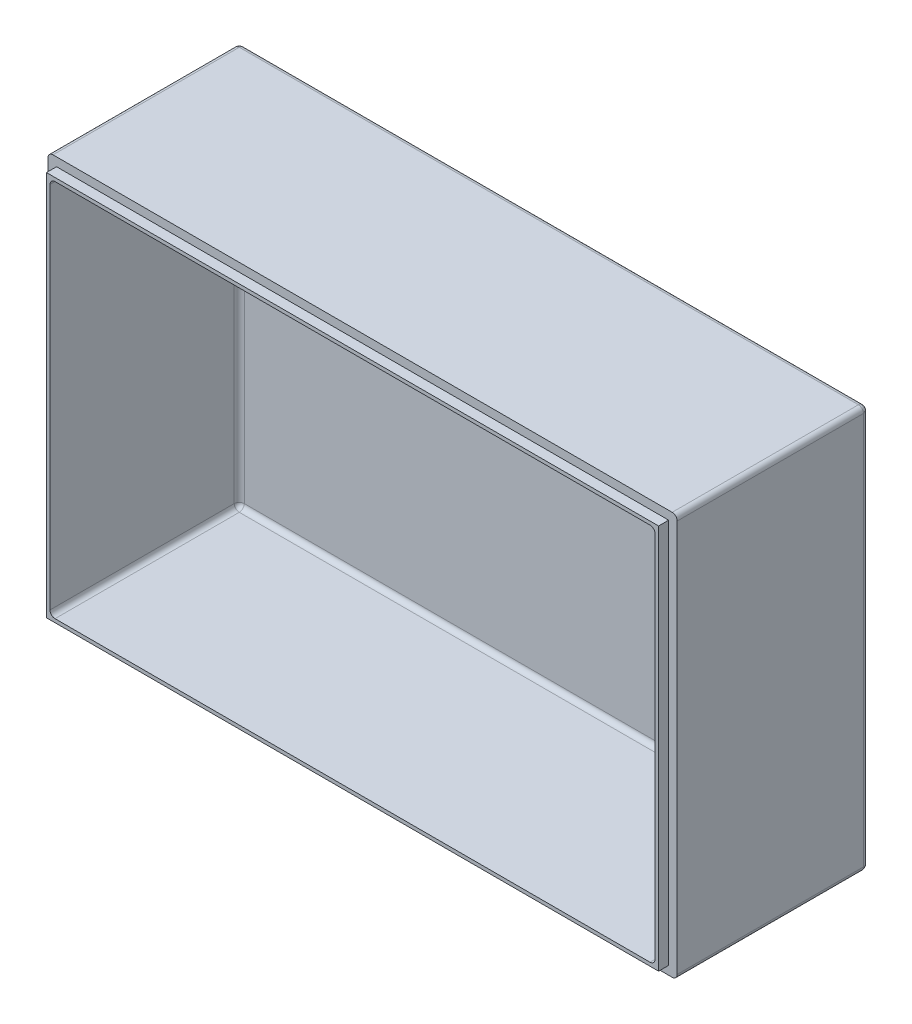
SolidWorks part; units mm, degrees
material "Резина"
ref_plane "Спереди" through (0, 0, 0) normal (0, 0, 1) x (1, 0, 0)
ref_plane "Сверху" through (0, 0, 0) normal (0, 1, 0) x (1, 0, 0)
ref_plane "Справа" through (0, 0, 0) normal (1, 0, 0) x (0, 0, -1)
sketch "Эскиз1" plane through (0, 0, 0) normal (0, 0, 1) x (1, 0, 0)
  line L1 (-62.5, 40) -> (62.5, 40)
  line L2 (-62.5, 40) -> (-62.5, -40)
  line L3 (-62.5, -40) -> (62.5, -40)
  line L4 (62.5, 40) -> (62.5, -40)
  line L5 (-62.5, 40) -> (62.5, -40) construction
  line L6 (-62.5, -40) -> (62.5, 40) construction
  point P0 (0, 0)
  dimension "D1" = 125
  dimension "D2" = 80
extrude "Бобышка-Вытянуть1" add sketch "Эскиз1" along normal blind 40
sketch "Эскиз2" plane through (0, 0, 40) normal (0, 0, 1) x (1, 0, 0)
  line L0 (62.5, 40) -> (-62.5, 40) construction
  line L1 (-60.1, 37.6) -> (60.1, 37.6)
  line L2 (-60.1, 37.6) -> (-60.1, -37.6)
  line L3 (-60.1, -37.6) -> (60.1, -37.6)
  line L4 (60.1, 37.6) -> (60.1, -37.6)
  line L5 (-60.1, 37.6) -> (60.1, -37.6) construction
  line L6 (-60.1, -37.6) -> (60.1, 37.6) construction
  line L7 (62.5, -40) -> (62.5, 40) construction
  point P0 (0, 0)
  dimension "D1" = 2.4
  dimension "D2" = 2.4
extrude "Вырез-Вытянуть1" cut sketch "Эскиз2" against normal blind 37.6
fillet "Скругление1" radius 1 8 edges at (62.5, -40, 20) (62.5, 40, 20) (62.5, 0, 0) (0, 40, 0) (-62.5, 40, 20) (-62.5, -40, 20) (0, -40, 0) (-62.5, 0, 0)
fillet "Скругление2" radius 1 8 edges at (60.1, 37.6, 21.2) (60.1, 0, 2.4) (60.1, -37.6, 21.2) (0, 37.6, 2.4) (-60.1, 37.6, 21.2) (0, -37.6, 2.4) (-60.1, -37.6, 21.2) (-60.1, 0, 2.4)
sketch "Эскиз3" plane through (0, 0, 0) normal (0, 0, -1) x (-1, 0, 0)
  line L0 (-61.5, 5) -> (59.5, 5) construction
  line L4 (-61.5, 39) -> (-61.5, -39) construction
  text T0 "Для\r\nЗСУ" font "Times New Roman" height 20
  dimension "D1" = 5
extrude "Вырез-Вытянуть2" [suppressed] cut sketch "Эскиз3" against normal blind 0.5
sketch "Эскиз4" plane through (62.5, 0, 0) normal (1, 0, 0) x (0, 0, -1)
  line L0 (0, 0) -> (-20.5, 0) construction
  line L1 (-20.5, -4) -> (-20.5, 4)
  line L2 (-20.5, 4) -> (-21.5858, 4)
  line L3 (-23.5, 2.0858) -> (-23.5, -2.0858)
  line L4 (-15.75, 0) -> (-20.5, 0) construction
  line L5 (-13, 6.5) -> (-18.5, 6.5)
  line L6 (-13, 6.5) -> (-13, -6.5)
  line L7 (-13, -6.5) -> (-18.5, -6.5)
  line L8 (-18.5, 6.5) -> (-18.5, -6.5)
  line L9 (-13, 6.5) -> (-18.5, -6.5) construction
  line L10 (-13, -6.5) -> (-18.5, 6.5) construction
  line L11 (-22.2929, 3.7071) -> (-23.2071, 2.7929)
  line L12 (-22.2929, -3.7071) -> (-23.2071, -2.7929)
  line L13 (-20.5, -4) -> (-21.5858, -4)
  arc A0 (-22.2929, -3.7071) -> (-21.5858, -4) centre (-21.5858, -3) ccw
  arc A1 (-23.2071, -2.7929) -> (-23.5, -2.0858) centre (-22.5, -2.0858) cw
  arc A2 (-23.2071, 2.7929) -> (-23.5, 2.0858) centre (-22.5, 2.0858) ccw
  arc A3 (-22.2929, 3.7071) -> (-21.5858, 4) centre (-21.5858, 3) cw
  point P5 (-15.75, 0)
  point P15 (-23.5, 0)
  point P18 (-22, -4)
  point P21 (-23.5, -2.5)
  point P24 (-23.5, 2.5)
  point P27 (-22, 4)
  dimension "D9" = 1
  dimension "D1" = 13
  dimension "D2" = 5.5
  dimension "D3" = 13
  dimension "D4" = 2
  dimension "D5" = 3
  dimension "D6" = 8
  dimension "D7" = 1.5
  dimension "D8" = 1.5
extrude "Вырез-Вытянуть3" [suppressed] cut sketch "Эскиз4" against normal blind 5
sketch "Эскиз5" plane through (60.1, 0, 0) normal (-1, 0, 0) x (0, 0, 1)
  line L0 (11.4, 0) -> (29.8169, 0) construction
  line L1 (11.4, 0) -> (11.4, -8.5)
  line L2 (11.4, -8.5) -> (13, -8.5)
  line L3 (13, -8.5) -> (13, 8.5)
  line L4 (11.4, 0) -> (11.4, 8.5)
  line L5 (11.4, 8.5) -> (13, 8.5)
  line L13 (0, -39) -> (0, 39) construction
  line L15 (11.4, -8.5) -> (21.4, -8.5)
  line L16 (11.4, -8.5) -> (11.4, -10.1)
  line L17 (11.4, -10.1) -> (21.4, -10.1)
  line L18 (21.4, -8.5) -> (21.4, -10.1)
  line L19 (11.4, -8.5) -> (21.4, -10.1) construction
  line L20 (11.4, -10.1) -> (21.4, -8.5) construction
  point P8 (16.4, -9.3)
  dimension "D1" = 1.6
  dimension "D2" = 17
  dimension "D3" = 8.5
  dimension "D4" = 13
  dimension "D5" = 17
  dimension "D6" = 1.6
  dimension "D7" = 10
  dimension "D8" = 11.4
extrude "Бобышка-Вытянуть2" [suppressed] add sketch "Эскиз5" along normal blind 20
sketch "Эскиз6" [suppressed] plane through (0, 0, 13) normal (0, 0, 1) x (1, 0, 0)
  line L0 (40.1, 0) -> (43.5026, 0) construction
  line L1 (40.1, -8.5) -> (40.1, 8.5) construction
  line L2 (40.1, 8.5) -> (60.1, 8.5) construction
  line L3 (43.6526, -1.5) -> (43.3526, -1.5)
  line L4 (43.9026, -1.25) -> (43.9026, 1.25)
  line L5 (43.6526, 1.5) -> (43.3526, 1.5)
  line L6 (43.1026, -1.25) -> (43.1026, 1.25)
  line L7 (43.9026, -1.5) -> (43.1026, 1.5) construction
  line L8 (43.9026, 1.5) -> (43.1026, -1.5) construction
  line L9 (45.9832, 6.5) -> (43.9832, 6.5)
  line L10 (46.2332, 6.75) -> (46.2332, 7.05)
  line L11 (45.9832, 7.3) -> (43.9832, 7.3)
  line L12 (43.7332, 6.75) -> (43.7332, 7.05)
  line L13 (46.2332, 6.5) -> (43.7332, 7.3) construction
  line L14 (46.2332, 7.3) -> (43.7332, 6.5) construction
  arc A0 (43.9026, 1.25) -> (43.6526, 1.5) centre (43.6526, 1.25) ccw
  arc A1 (43.1026, 1.25) -> (43.3526, 1.5) centre (43.3526, 1.25) cw
  arc A2 (43.3526, -1.5) -> (43.1026, -1.25) centre (43.3526, -1.25) cw
  arc A3 (43.9026, -1.25) -> (43.6526, -1.5) centre (43.6526, -1.25) cw
  arc A4 (43.7332, 7.05) -> (43.9832, 7.3) centre (43.9832, 7.05) cw
  arc A5 (43.9832, 6.5) -> (43.7332, 6.75) centre (43.9832, 6.75) cw
  arc A6 (46.2332, 7.05) -> (45.9832, 7.3) centre (45.9832, 7.05) ccw
  arc A7 (46.2332, 6.75) -> (45.9832, 6.5) centre (45.9832, 6.75) cw
  point P8 (44.9832, 6.9)
  point P15 (44.9832, 7.3)
  dimension "D7" = 0.25
  dimension "D8" = 0.25
  dimension "D1" = 0.8
  dimension "D2" = 3
  dimension "D3" = 8.5
  dimension "D4" = 0.8
  dimension "D5" = 2.5
  dimension "D6" = 1.2
extrude "Бобышка-Вытянуть3" [suppressed] add sketch "Эскиз6" along normal blind 8
sketch "Эскиз7" plane through (0, 0, 40) normal (0, 0, 1) x (1, 0, 0)
  line L4 (60.8, -38.3) -> (60.8, 38.3)
  line L5 (60.8, 38.3) -> (-60.8, 38.3)
  line L6 (-60.8, 38.3) -> (-60.8, -38.3)
  line L7 (-60.8, -38.3) -> (60.8, -38.3)
  line L8 (-61.5, -40) -> (61.5, -40)
  line L9 (62.5, -39) -> (62.5, 39)
  line L10 (61.5, 40) -> (-61.5, 40)
  line L11 (-62.5, 39) -> (-62.5, -39)
  line L12 (-61.5, -40) -> (61.5, -40)
  line L13 (62.5, -39) -> (62.5, 39)
  line L14 (61.5, 40) -> (-61.5, 40)
  line L15 (-62.5, 39) -> (-62.5, -39)
  circle A0 centre (0, 0) radius 6.5426
  arc A4 (60.8, 38.3) -> (60.8, 38.3) centre (60.8, 38.3) ccw
  arc A5 (-60.8, 38.3) -> (-60.8, 38.3) centre (-60.8, 38.3) ccw
  arc A6 (-60.8, -38.3) -> (-60.8, -38.3) centre (-60.8, -38.3) ccw
  arc A7 (60.8, -38.3) -> (60.8, -38.3) centre (60.8, -38.3) ccw
  arc A8 (61.5, -40) -> (62.5, -39) centre (61.5, -39) ccw
  arc A9 (62.5, 39) -> (61.5, 40) centre (61.5, 39) ccw
  arc A10 (-61.5, 40) -> (-62.5, 39) centre (-61.5, 39) ccw
  arc A11 (-62.5, -39) -> (-61.5, -40) centre (-61.5, -39) ccw
  arc A12 (61.5, -40) -> (62.5, -39) centre (61.5, -39) ccw
  arc A13 (62.5, 39) -> (61.5, 40) centre (61.5, 39) ccw
  arc A14 (-61.5, 40) -> (-62.5, 39) centre (-61.5, 39) ccw
  arc A15 (-62.5, -39) -> (-61.5, -40) centre (-61.5, -39) ccw
  line M17 (-61.5, -40) -> (61.5, -40)
  arc M18 (61.5, -40) -> (62.5, -39) centre (61.5, -39) ccw
  line M19 (62.5, -39) -> (62.5, 39)
  arc M20 (62.5, 39) -> (61.5, 40) centre (61.5, 39) ccw
  line M21 (61.5, 40) -> (-61.5, 40)
  arc M22 (-61.5, 40) -> (-62.5, 39) centre (-61.5, 39) ccw
  line M23 (-62.5, 39) -> (-62.5, -39)
  arc M24 (-62.5, -39) -> (-61.5, -40) centre (-61.5, -39) ccw
  dimension "D1" = 0
  dimension "D2" = 1.7
extrude "Вырез-Вытянуть4" cut sketch "Эскиз7" against normal blind 2 contours L7 L6 L5 L4 M24 M17 M18 M19 M20 M21 M22 M23
